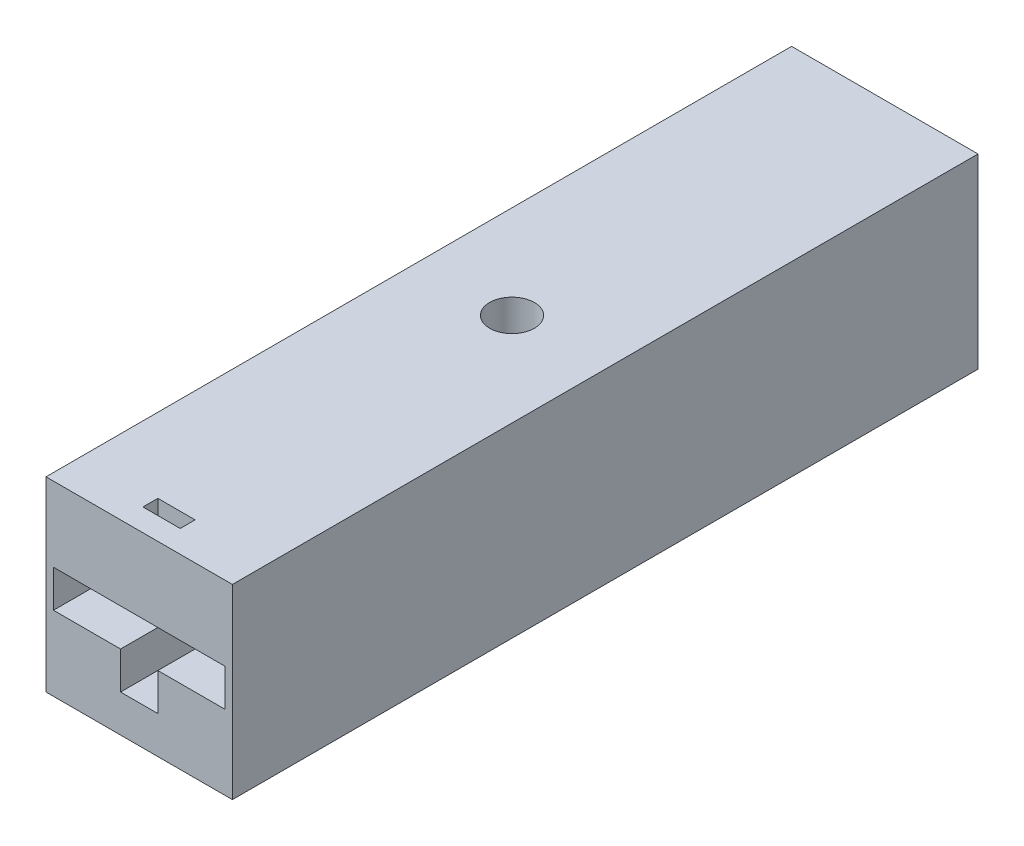
SolidWorks part; units mm, degrees
ref_plane "Plan de face" through (0, 0, 0) normal (0, 0, 1) x (1, 0, 0)
ref_plane "Plan de dessus" through (0, 0, 0) normal (0, 1, 0) x (1, 0, 0)
ref_plane "Plan de droite" through (0, 0, 0) normal (1, 0, 0) x (0, 0, -1)
sketch "Esquisse1" plane through (0, 0, 0) normal (0, 0, 1) x (1, 0, 0)
  line L1 (-12.5, -12.5) -> (12.5, -12.5)
  line L2 (-12.5, -12.5) -> (-12.5, 12.5)
  line L3 (-12.5, 12.5) -> (12.5, 12.5)
  line L4 (12.5, -12.5) -> (12.5, 12.5)
  line L5 (-12.5, -12.5) -> (12.5, 12.5) construction
  line L6 (-12.5, 12.5) -> (12.5, -12.5) construction
  point P0 (0, 0)
  dimension "D1" = 25
  dimension "D2" = 25
extrude "Boss.-Extru.1" add sketch "Esquisse1" along normal blind 100
sketch "Esquisse3" plane through (0, 0, 100) normal (0, 0, 1) x (1, 0, 0)
  line L0 (-11.5, 2.5) -> (-11.5, -2.5) construction
  line L1 (-11.5, -2.5) -> (11.5, -2.5) construction
  line L2 (-11.5, -2.5) -> (-11.5, 2.5) construction
  line L3 (-11.5, 2.5) -> (11.5, 2.5) construction
  line L4 (11.5, -2.5) -> (11.5, 2.5) construction
  line L5 (-11.5, -2.5) -> (11.5, 2.5) construction
  line L6 (-11.5, 2.5) -> (11.5, -2.5) construction
  line L7 (-11.5, 2.5) -> (11.5, 2.5)
  line L8 (-2.5, -2.5) -> (2.5, -2.5) construction
  line L9 (-2.5, -2.5) -> (-2.5, -7.5) construction
  line L10 (-2.5, -7.5) -> (2.5, -7.5) construction
  line L11 (2.5, -2.5) -> (2.5, -7.5) construction
  line L12 (11.5, 2.5) -> (11.5, -2.5)
  line L13 (11.5, -2.5) -> (2.5, -2.5)
  line L14 (2.5, -2.5) -> (2.5, -7.5)
  line L15 (2.5, -7.5) -> (-2.5, -7.5)
  line L16 (-2.5, -7.5) -> (-2.5, -2.5)
  line L17 (-2.5, -2.5) -> (-11.5, -2.5)
  line L18 (-11.5, -2.5) -> (-11.5, 2.5)
  point P0 (0, 0)
  point P10 (0, -7.5)
  dimension "D1" = 23
  dimension "D2" = 5
  dimension "D3" = 5
  dimension "D4" = 5
extrude "Enlèv. mat.-Extru.2" cut sketch "Esquisse3" against normal blind 10
sketch "Esquisse4" plane through (0, 0, 0) normal (0, 0, 1) x (1, 0, 0)
  line L0 (2.5, 11.5) -> (-2.5, 11.5)
  line L1 (-2.5, -11.5) -> (2.5, -11.5) construction
  line L2 (-2.5, -11.5) -> (-2.5, 11.5) construction
  line L3 (-2.5, 11.5) -> (2.5, 11.5) construction
  line L5 (2.5, 2.5) -> (7.5, 2.5)
  line L7 (2.5, -2.5) -> (7.5, -2.5) construction
  line L9 (2.5, 2.5) -> (7.5, 2.5) construction
  line L10 (7.5, -2.5) -> (7.5, 2.5) construction
  line L11 (-2.5, 11.5) -> (-2.5, -11.5)
  line L12 (-2.5, -11.5) -> (2.5, -11.5)
  line L13 (2.5, -11.5) -> (2.5, -2.5)
  line L14 (2.5, -2.5) -> (7.5, -2.5)
  line L15 (7.5, -2.5) -> (7.5, 2.5)
  line L16 (7.5, 2.5) -> (2.5, 2.5)
  line L17 (2.5, 2.5) -> (2.5, 11.5)
  line L18 (7.5, -2.5) -> (2.5, -2.5)
  line L19 (-2.5, 11.5) -> (2.5, -11.5) construction
  line L20 (-2.5, -11.5) -> (2.5, 11.5) construction
  point P0 (0, 0)
  point P10 (7.5, 0)
  point P11 (0, 0)
  dimension "D1" = 5
  dimension "D2" = 23
  dimension "D3" = 5
  dimension "D4" = 5
sketch "Esquisse9" plane through (0, 12.5, 0) normal (0, 1, 0) x (1, 0, 0)
  line L0 (-12.5, -100) -> (12.5, 0) construction
  circle A0 centre (0, -50) radius 3
extrude "Enlèv. mat.-Extru.4" cut sketch "Esquisse9" against normal blind 54
extrude "Enlèv. mat.-Extru.5" cut sketch "Esquisse4" along normal blind 10 contours L17 L0 L11 L12 L13 L14 L15 L16
sketch "Esquisse10" plane through (0, 12.5, 0) normal (0, 1, 0) x (1, 0, 0)
  line L0 (0, -100) -> (0, -96) construction
  line L1 (12.5, -100) -> (-12.5, -100) construction
  line L3 (-2.5, -97) -> (2.5, -97)
  line L4 (-2.5, -97) -> (-2.5, -95)
  line L5 (-2.5, -95) -> (2.5, -95)
  line L6 (2.5, -97) -> (2.5, -95)
  line L7 (-2.5, -97) -> (2.5, -95) construction
  line L8 (-2.5, -95) -> (2.5, -97) construction
  dimension "D1" = 4
extrude "Enlèv. mat.-Extru.6" cut sketch "Esquisse10" against normal blind 13
sketch "Esquisse11" plane through (-12.5, 0, 0) normal (-1, 0, 0) x (0, 0, 1)
  line L0 (0, 0) -> (4, 0) construction
  line L2 (3, -2.5) -> (5, -2.5)
  line L3 (3, -2.5) -> (3, 2.5)
  line L4 (3, 2.5) -> (5, 2.5)
  line L5 (5, -2.5) -> (5, 2.5)
  line L6 (3, -2.5) -> (5, 2.5) construction
  line L7 (3, 2.5) -> (5, -2.5) construction
  dimension "D1" = 2
  dimension "D2" = 5
extrude "Enlèv. mat.-Extru.7" cut sketch "Esquisse11" against normal blind 13
